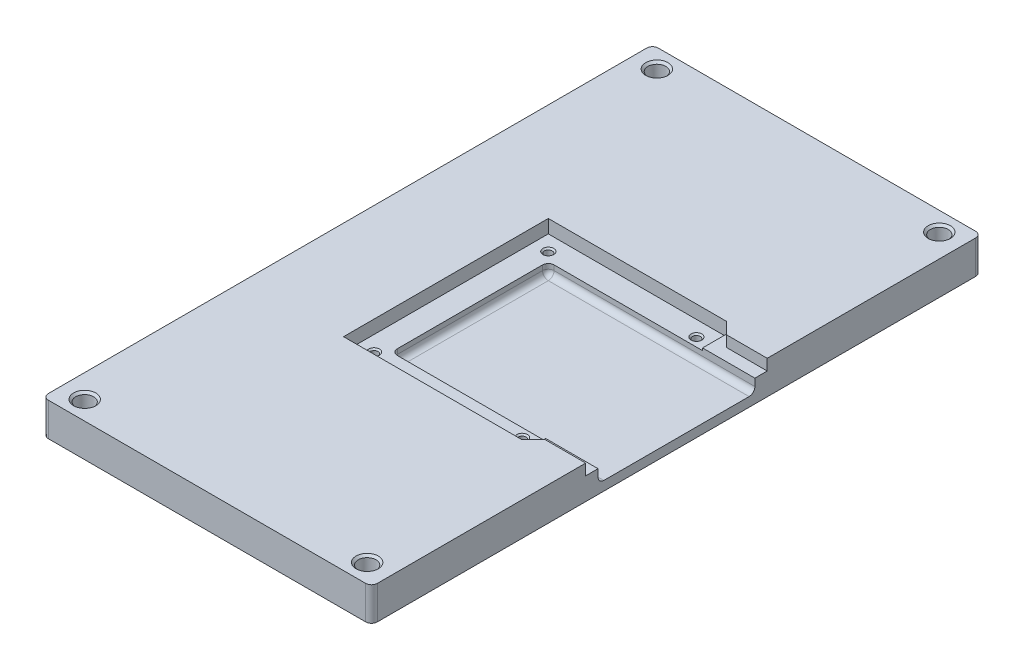
SolidWorks part; units mm, degrees
ref_plane "Front Plane" through (0, 0, 0) normal (0, 0, 1) x (1, 0, 0)
ref_plane "Top Plane" through (0, 0, 0) normal (0, 1, 0) x (1, 0, 0)
ref_plane "Right Plane" through (0, 0, 0) normal (1, 0, 0) x (0, 0, -1)
sketch "Sketch1" plane through (0, 0, 0) normal (0, 1, 0) x (1, 0, 0)
  line L0 (0, -90) -> (0, 90) construction
  line L1 (56.625, 90) -> (-56.625, 90) construction
  line L2 (-56.625, 90) -> (-56.625, -90)
  line L3 (-56.625, 0) -> (56.625, 0) construction
  line L4 (-56.625, 90) -> (-56.625, 103)
  line L5 (-54.625, 105) -> (54.625, 105)
  line L6 (0, 105) -> (0, 90) construction
  line L7 (56.625, 90) -> (56.625, 103)
  line L8 (56.625, 90) -> (56.625, -90)
  line L9 (0, -105) -> (0, -90) construction
  line L10 (56.625, -90) -> (-56.625, -90) construction
  line L11 (56.625, -90) -> (56.625, -103)
  line L12 (-54.625, -105) -> (54.625, -105)
  line L13 (-56.625, -90) -> (-56.625, -103)
  line L14 (-56.625, 93) -> (56.625, 93) construction
  circle A1 centre (-48.625, 98.5) radius 3.075 construction
  circle A2 centre (48.625, 98.5) radius 3.075 construction
  circle A5 centre (48.625, -98.5) radius 3.075 construction
  circle A6 centre (-48.625, -98.5) radius 3.075 construction
  arc A8 (-54.625, -105) -> (-56.625, -103) centre (-54.625, -103) cw
  arc A9 (56.625, -103) -> (54.625, -105) centre (54.625, -103) cw
  arc A10 (56.625, 103) -> (54.625, 105) centre (54.625, 103) ccw
  arc A11 (-56.625, 103) -> (-54.625, 105) centre (-54.625, 103) cw
  point P24 (0, 0)
  point P36 (-56.625, -105)
  point P39 (56.625, -105)
  point P42 (56.625, 105)
  point P45 (-56.625, 105)
  dimension "D10" = 2
  dimension "D3" = 6.15
  dimension "D1" = 56.625
  dimension "D2" = 90
  dimension "D4" = 6.5
  dimension "D6" = 8
  dimension "D7" = 8.5
  dimension "D8" = 12
  dimension "D9" = 3
  dimension "D11" = 105
extrude "Boss-Extrude1" add sketch "Sketch1" along normal blind 11.5
sketch "Sketch3" plane through (0, 11.5, 0) normal (0, 1, 0) x (1, 0, 0)
  line L0 (0, 0) -> (-56.625, 0) construction
  line L1 (-56.625, 103) -> (-56.625, -103) construction
  line L2 (0, 0) -> (0, 105) construction
  line L3 (54.625, 105) -> (-54.625, 105) construction
  line L4 (3.96, -16.3) -> (3.96, 16.3)
  line L5 (-2.46, -17.8) -> (2.46, -17.8)
  line L6 (-3.96, 16.3) -> (-3.96, -16.3)
  line L7 (2.46, 17.8) -> (-2.46, 17.8)
  line L8 (0, 17.8) -> (0, -17.8) construction
  line L9 (13.25, 0) -> (0, 0) construction
  line L10 (16.15, 10.025) -> (10.35, 10.025)
  line L11 (16.15, 10.025) -> (16.15, -10.025)
  line L12 (16.15, -10.025) -> (10.35, -10.025)
  line L13 (10.35, 10.025) -> (10.35, -10.025)
  line L14 (16.15, 10.025) -> (10.35, -10.025) construction
  line L15 (16.15, -10.025) -> (10.35, 10.025) construction
  line L16 (13.25, 0) -> (13.25, 10.025) construction
  line L17 (-16.15, 10.025) -> (-16.15, -10.025)
  line L18 (-16.15, -10.025) -> (-10.35, -10.025)
  line L23 (-16.15, 10.025) -> (-10.35, 10.025)
  line L24 (-10.35, 10.025) -> (-10.35, -10.025)
  arc A0 (-2.46, 17.8) -> (-3.96, 16.3) centre (-2.46, 16.3) ccw
  arc A1 (3.96, 16.3) -> (2.46, 17.8) centre (2.46, 16.3) ccw
  arc A2 (2.46, -17.8) -> (3.96, -16.3) centre (2.46, -16.3) ccw
  arc A3 (-3.96, -16.3) -> (-2.46, -17.8) centre (-2.46, -16.3) ccw
  point P9 (0, 0)
  point P23 (0, 0)
  dimension "D2" = 1.5
  dimension "D1" = 35.6
  dimension "D3" = 7.92
  dimension "D4" = 20.05
  dimension "D5" = 5.8
  dimension "D6" = 13.25
sketch "Sketch4" plane through (0, 11.5, 0) normal (0, 1, 0) x (1, 0, 0)
  circle A0 centre (-48.625, -98.5) radius 3.075 construction
  circle A1 centre (48.625, -98.5) radius 3.075 construction
  circle A2 centre (48.625, 98.5) radius 3.075 construction
  circle A5 centre (-48.625, 98.5) radius 3.075 construction
  circle A8 centre (-48.625, -98.5) radius 3.075
  circle A9 centre (48.625, -98.5) radius 3.075
  circle A10 centre (48.625, 98.5) radius 3.075
  circle A13 centre (-48.625, 98.5) radius 3.075
extrude "Cut-Extrude1" cut sketch "Sketch4" against normal blind 6
sketch "Sketch21" plane through (0, 11.5, 0) normal (0, 1, 0) x (1, 0, 0)
  line L0 (38.5, 35) -> (-22.5, 35) construction
  line L1 (38.5, 35) -> (42.5, 31) construction
  line L2 (-22.5, 35) -> (-22.5, -35) construction
  line L3 (-22.5, 0) -> (0, 0) construction
  line L4 (0, 0) -> (38.5, 0) construction
  line L5 (38.5, -35) -> (38.5, 35) construction
  line L6 (38.5, -35) -> (-22.5, -35) construction
  line L7 (42.5, 31) -> (56.625, 31) construction
  line L8 (56.625, -103) -> (56.625, 103) construction
  line L9 (56.625, 31) -> (56.625, -31)
  line L10 (56.625, 0) -> (38.5, 0) construction
  line L11 (42.5, -31) -> (56.625, -31) construction
  line L12 (38.5, -35) -> (42.5, -31) construction
  line L13 (42.6036, 31.25) -> (56.625, 31.25)
  line L14 (38.6036, 35.25) -> (42.6036, 31.25)
  line L15 (38.6036, 35.25) -> (-22.75, 35.25)
  line L16 (-22.75, 35.25) -> (-22.75, -35.25)
  line L17 (38.6036, -35.25) -> (-22.75, -35.25)
  line L18 (38.6036, -35.25) -> (42.6036, -31.25)
  line L19 (42.6036, -31.25) -> (56.625, -31.25)
  line L20 (56.625, -31.25) -> (56.625, -31)
  line L21 (56.625, 31) -> (56.625, 31.25)
  circle A0 centre (-17.5, 30) radius 1.6 construction
  circle A1 centre (33.5, 30) radius 1.6 construction
  circle A2 centre (33.5, -30) radius 1.6 construction
  circle A3 centre (-17.5, -30) radius 1.6 construction
  dimension "D8" = 3.2
  dimension "D1" = 22.5
  dimension "D2" = 61
  dimension "D3" = 35
  dimension "D4" = 5
  dimension "D5" = 5
  dimension "D6" = 5
  dimension "D7" = 5
  dimension "D9" = 45
  dimension "D10" = 4
  dimension "D12" = 14.125
  dimension "D11" = 0.25
extrude "Cut-Extrude6" cut sketch "Sketch21" against normal blind 4.6
sketch "Sketch24" plane through (0, 6.9, 0) normal (0, 1, 0) x (1, 0, 0)
  line L0 (56.625, 27) -> (-14.5, 27)
  line L2 (-14.5, 27) -> (-14.5, -27)
  line L3 (-14.5, -27) -> (56.625, -27)
  line L4 (56.625, -27) -> (56.625, 27)
  line L8 (38.5, 35) -> (-22.5, 35) construction
  line L10 (-22.5, 35) -> (-22.5, -35) construction
  line L11 (38.5, -35) -> (-22.5, -35) construction
  line L12 (56.625, -31.25) -> (56.625, 31.25) construction
  dimension "D1" = 8
  dimension "D2" = 8
  dimension "D3" = 8
extrude "Cut-Extrude3" cut sketch "Sketch24" against normal blind 3.7 and the other way through all
sketch "Sketch25" plane through (0, 6.9, 0) normal (0, 1, 0) x (1, 0, 0)
  circle A0 centre (33.5, 30) radius 1.35
  circle A1 centre (-17.5, 30) radius 1.35
  circle A2 centre (33.5, -30) radius 1.35
  circle A3 centre (-17.5, -30) radius 1.35
  dimension "D1" = 2.7
extrude "Cut-Extrude4" cut sketch "Sketch25" against normal blind 5
chamfer "Chamfer4" distance 0.5 angle 45 4 edges at (-17.5, 6.9, 31.35) (33.5, 6.9, 31.35) (33.5, 6.9, -28.65) (-17.5, 6.9, -28.65)
fillet "Fillet1" radius 2 5 edges at (21.0625, 3.2, 27) (-14.5, 5.05, 27) (-14.5, 5.05, -27) (-14.5, 3.2, 0) (21.0625, 3.2, -27)
sketch "Sketch26" plane through (0, 6.9, 0) normal (0, 1, 0) x (1, 0, 0)
  line L0 (0, 0) -> (56.625, 0) construction
  line L1 (56.625, -25) -> (56.625, 25) construction
  line L2 (38.6036, 35.25) -> (38.6036, 27)
  line L3 (56.625, 27) -> (-12.5, 27) construction
  line L4 (38.6036, 27) -> (56.625, 27)
  line L5 (56.625, 27) -> (56.625, 31.25)
  line L6 (56.625, 31.25) -> (42.6036, 31.25)
  line L7 (42.6036, 31.25) -> (38.6036, 35.25)
  line L8 (42.6036, -31.25) -> (38.6036, -35.25)
  line L9 (56.625, -31.25) -> (42.6036, -31.25)
  line L10 (56.625, -27) -> (56.625, -31.25)
  line L11 (38.6036, -27) -> (56.625, -27)
  line L12 (38.6036, -35.25) -> (38.6036, -27)
extrude "Boss-Extrude2" add sketch "Sketch26" along normal blind 0.8
chamfer "Chamfer5" distance 0.75 angle 45 4 edges at (48.625, 11.5, 101.575) (-48.625, 11.5, 101.575) (-48.625, 11.5, -95.425) (48.625, 11.5, -95.425)
equation "\"D5@Sketch21\"=\"D4@Sketch21\""
equation "\"D6@Sketch21\"=\"D4@Sketch21\""
equation "\"D7@Sketch21\"=\"D4@Sketch21\""
equation "\"D2@Sketch24\"=\"D1@Sketch24\""
equation "\"D3@Sketch24\"=\"D1@Sketch24\""
